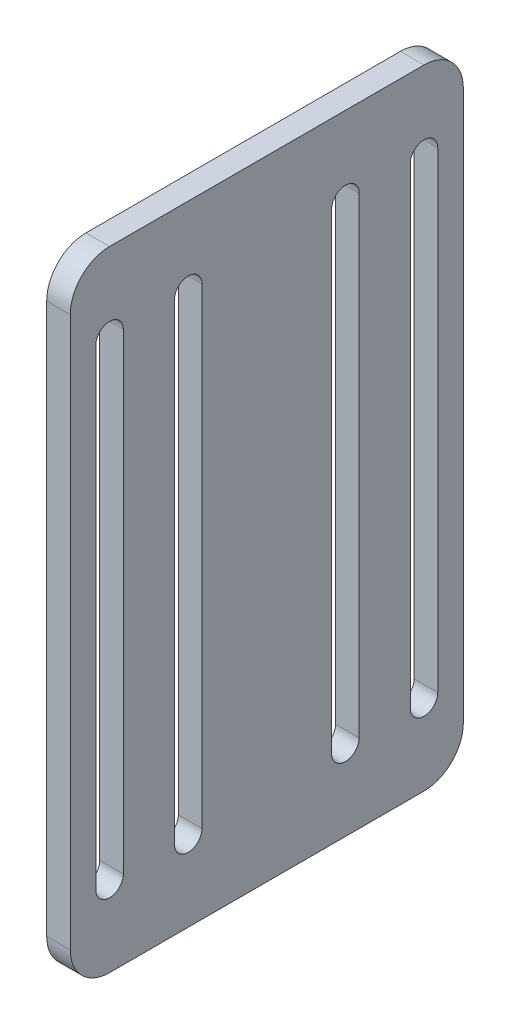
SolidWorks part; units mm, degrees
ref_plane "前视基准面" through (0, 0, 0) normal (0, 0, 1) x (1, 0, 0)
ref_plane "上视基准面" through (0, 0, 0) normal (0, 1, 0) x (1, 0, 0)
ref_plane "右视基准面" through (0, 0, 0) normal (1, 0, 0) x (0, 0, -1)
sketch "草图1" plane through (0, 0, 0) normal (1, 0, 0) x (0, 0, -1)
  line L0 (-20, 40) -> (-20, -40) construction
  line L1 (-25, 40) -> (25, 40)
  line L2 (-25, 40) -> (-25, -40)
  line L3 (-25, -40) -> (25, -40)
  line L4 (25, 40) -> (25, -40)
  line L5 (-25, 40) -> (25, -40) construction
  line L6 (-25, -40) -> (25, 40) construction
  line L7 (-10, -40) -> (-10, 40) construction
  line L8 (10, 40) -> (10, -40) construction
  line L9 (20, -40) -> (20, 40) construction
  line L10 (0, 40) -> (0, -40) construction
  line L11 (-21.75, 30) -> (-21.75, -30)
  line L12 (-18.25, -30) -> (-18.25, 30)
  line L13 (-11.75, 30) -> (-11.75, -30)
  line L14 (-8.25, 30) -> (-8.25, -30)
  line L15 (-1.75, 30) -> (-1.75, -30)
  line L16 (1.75, -30) -> (1.75, 30)
  line L17 (8.25, 30) -> (8.25, -30)
  line L18 (11.75, -30) -> (11.75, 30)
  line L19 (21.75, -30) -> (21.75, 30)
  line L20 (18.25, 30) -> (18.25, -30)
  line L21 (-25, 30) -> (25, 30) construction
  line L22 (-25, -30) -> (25, -30) construction
  circle A0 centre (-10, 30) radius 1.75
  circle A1 centre (-20, 30) radius 1.75
  circle A2 centre (-20, -30) radius 1.75
  circle A3 centre (-10, -30) radius 1.75
  circle A4 centre (0, -30) radius 1.75
  circle A5 centre (10, -30) radius 1.75
  circle A7 centre (20, 30) radius 1.75
  circle A8 centre (10, 30) radius 1.75
  circle A9 centre (0, 30) radius 1.75
  circle A10 centre (20, -30) radius 1.75
  point P0 (0, 0)
  point P52 (18.25, -38.3793)
  dimension "D7" = 3.5
  dimension "D8" = 3.5
  dimension "D9" = 3.5
  dimension "D10" = 3.5
  dimension "D11" = 3.5
  dimension "D12" = 3.5
  dimension "D13" = 3.5
  dimension "D14" = 3.5
  dimension "D15" = 3.5
  dimension "D16" = 3.5
  dimension "D17" = 50
  dimension "D18" = 10
  dimension "D2" = 80
  dimension "D3" = 5
  dimension "D4" = 5
  dimension "D5" = 10
  dimension "D6" = 10
  dimension "D19" = 10
extrude "凸台-拉伸1" add sketch "草图1" along normal blind 3
fillet "圆角1" radius 5 4 edges at (1.5, -40, -25) (1.5, -40, 25) (1.5, 40, 25) (1.5, 40, -25)
